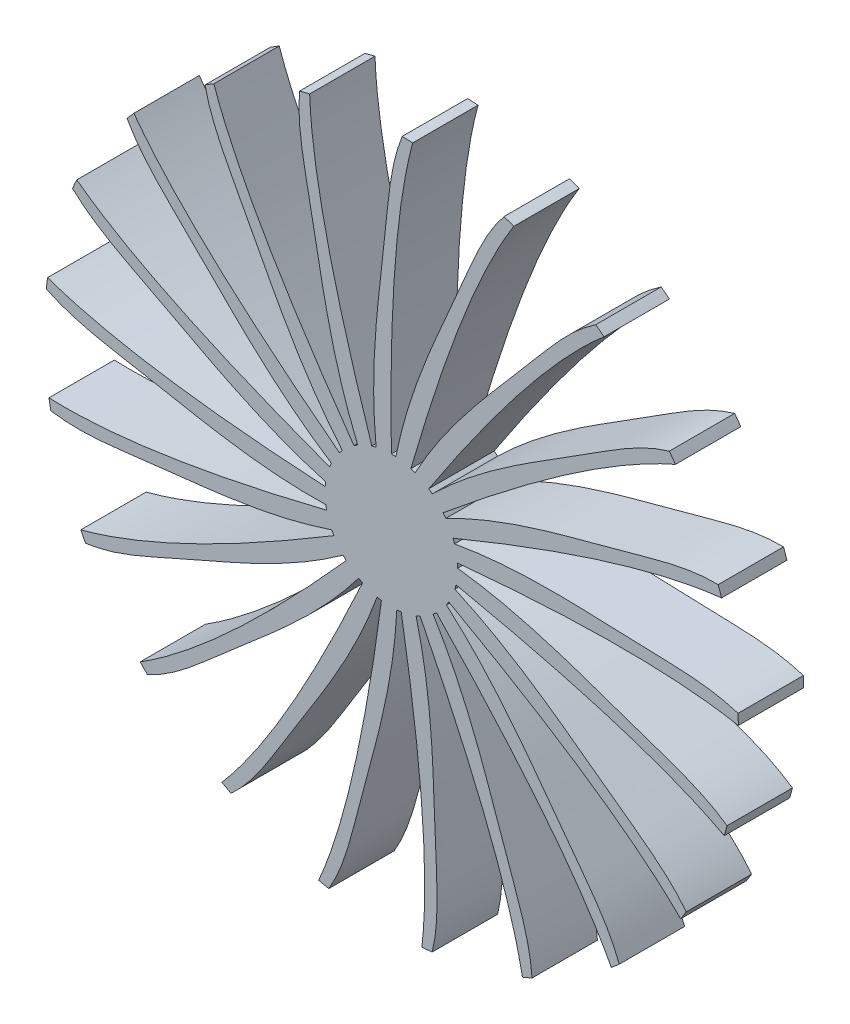
SolidWorks part; units mm, degrees
ref_plane "Front Plane" through (0, 0, 0) normal (0, 0, 1) x (1, 0, 0)
ref_plane "Top Plane" through (0, 0, 0) normal (0, 1, 0) x (1, 0, 0)
ref_plane "Right Plane" through (0, 0, 0) normal (1, 0, 0) x (0, 0, -1)
sketch "Sketch1" plane through (0, 0, 0) normal (0, 0, 1) x (1, 0, 0)
  line L0 (0, 30.4353) -> (0, 70.6877) construction
  arc A0 (9.785, 158.9473) -> (5, 159.1697) centre (0, 0) ccw
  arc A1 (-15.0149, -26.4738) -> (-13.2054, -27.4213) centre (0, 0) ccw
  arc A2 (56.2008, 149.0016) -> (51.694, 150.6245) centre (0, 0) ccw
  arc A3 (97.6229, 125.8164) -> (93.7947, 128.6956) centre (0, 0) ccw
  arc A4 (130.3708, 91.4518) -> (127.5613, 95.3315) centre (0, 0) ccw
  arc A5 (151.5347, 48.9614) -> (149.9936, 53.4969) centre (0, 0) ccw
  arc A6 (159.2341, 2.1205) -> (159.0983, 6.9087) centre (0, 0) ccw
  arc A7 (152.7848, -44.9087) -> (154.0664, -40.2932) centre (0, 0) ccw
  arc A8 (132.7599, -87.9477) -> (135.345, -83.915) centre (0, 0) ccw
  arc A9 (100.9387, -123.1721) -> (104.5976, -120.0805) centre (0, 0) ccw
  arc A10 (60.1487, -147.4521) -> (64.5563, -145.5764) centre (0, 0) ccw
  arc A11 (14.0142, -158.6304) -> (18.7789, -158.1371) centre (0, 0) ccw
  arc A12 (-33.3655, -155.7136) -> (-28.6672, -156.6467) centre (0, 0) ccw
  arc A13 (-77.7806, -138.961) -> (-73.566, -141.2375) centre (0, 0) ccw
  arc A14 (-115.2845, -109.8612) -> (-111.9282, -113.2788) centre (0, 0) ccw
  arc A15 (-142.5449, -70.9996) -> (-140.345, -75.2547) centre (0, 0) ccw
  arc A16 (-157.1395, -25.8295) -> (-156.2916, -30.544) centre (0, 0) ccw
  arc A17 (-157.7716, 21.6357) -> (-158.351, 16.8808) centre (0, 0) ccw
  arc A18 (-144.385, 67.1785) -> (-146.3402, 62.8056) centre (0, 0) ccw
  arc A19 (-118.1692, 106.7522) -> (-121.3264, 103.1498) centre (0, 0) ccw
  arc A20 (-81.4535, 136.8405) -> (-85.5323, 134.3288) centre (0, 0) ccw
  arc A21 (-37.5003, 154.7699) -> (-42.1382, 153.572) centre (0, 0) ccw
  arc A22 (-22.1511, -20.8719) -> (-20.7013, -22.3107) centre (0, 0) ccw
  arc A23 (2.5073, -30.3319) -> (4.5361, -30.0954) centre (0, 0) ccw
  arc A24 (-6.5446, -29.7233) -> (-4.5361, -30.0954) centre (0, 0) ccw
  arc A25 (11.3364, -28.2453) -> (13.2054, -27.4213) centre (0, 0) ccw
  arc A26 (19.1582, -23.649) -> (20.7013, -22.3107) centre (0, 0) ccw
  arc A27 (25.2777, -16.9513) -> (26.3578, -15.2177) centre (0, 0) ccw
  arc A28 (29.1511, -8.7475) -> (29.6722, -6.7725) centre (0, 0) ccw
  arc A29 (-27.3191, -13.4154) -> (-26.3578, -15.2177) centre (0, 0) ccw
  arc A30 (-30.0597, -4.767) -> (-29.6722, -6.7725) centre (0, 0) ccw
  arc A31 (-30.1293, 4.3051) -> (-30.3502, 2.2744) centre (0, 0) ccw
  arc A32 (-22.4689, 20.5295) -> (-23.7953, 18.9761) centre (0, 0) ccw
  arc A33 (-27.5218, 12.9946) -> (-28.3314, 11.1193) centre (0, 0) ccw
  arc A34 (-15.4195, 26.2402) -> (-17.1448, 25.1468) centre (0, 0) ccw
  arc A35 (-7, 29.6194) -> (-8.971, 29.0832) centre (0, 0) ccw
  arc A36 (2.0415, 30.3668) -> (0, 30.4353) centre (0, 0) ccw
  arc A37 (10.9015, 28.4159) -> (8.971, 29.0832) centre (0, 0) ccw
  arc A38 (18.7929, 23.9402) -> (17.1448, 25.1468) centre (0, 0) ccw
  arc A39 (25.0145, 17.3373) -> (23.7953, 18.9761) centre (0, 0) ccw
  arc A40 (29.0135, 9.1939) -> (28.3314, 11.1193) centre (0, 0) ccw
  arc A41 (30.4344, 0.2336) -> (30.3502, 2.2744) centre (0, 0) ccw
  spline S0 degree 3 poles (-7, 29.6194) (-9.6924, 56.721) (-6.6225, 83.7904) (-1.6795, 126.6297) (-0.3347, 146.1346) (5, 159.1697) knots 0 0 0 0 0.569376 0.669376 1 1 1 1
  spline S1 degree 2 poles (0, 30.4353) (-1.6186, 116.9207) (9.785, 158.9473) knots 0 0 0 1 1 1
  spline S2 degree 3 poles (2.0415, 30.3668) (7.457, 57.0579) (18.3694, 82.0198) (35.7199, 121.4989) (42.7542, 139.7409) (51.694, 150.6245) knots 0 0 0 0 0.569376 0.669376 1 1 1 1
  spline S3 degree 2 poles (8.971, 29.0832) (32.9163, 112.2034) (56.2008, 149.0016) knots 0 0 0 1 1 1
  spline S4 degree 3 poles (10.9015, 28.4159) (23.9438, 52.325) (41.7291, 72.9615) (69.9454, 105.5725) (82.0441, 120.9306) (93.7947, 128.6956) knots 0 0 0 0 0.569376 0.669376 1 1 1 1
  spline S5 degree 2 poles (17.1448, 25.1468) (64.5264, 97.5162) (97.6229, 125.8164) knots 0 0 0 1 1 1
  spline S6 degree 3 poles (18.7929, 23.9402) (38.3031, 42.9428) (61.3809, 57.4201) (97.9559, 80.2654) (114.044, 91.3751) (127.5613, 95.3315) knots 0 0 0 0 0.569376 0.669376 1 1 1 1
  spline S7 degree 2 poles (23.7953, 18.9761) (90.4031, 74.1644) (130.3708, 91.4518) knots 0 0 0 1 1 1
  spline S8 degree 3 poles (25.0145, 17.3373) (49.259, 29.7449) (75.5788, 36.7768) (117.2627, 47.8264) (135.9106, 53.7005) (149.9936, 53.4969) knots 0 0 0 0 0.569376 0.669376 1 1 1 1
  spline S9 degree 2 poles (28.3314, 11.1193) (108.2471, 44.2227) (151.5347, 48.9614) knots 0 0 0 1 1 1
  spline S10 degree 3 poles (29.0135, 9.1939) (55.8381, 13.9041) (83.0612, 12.8656) (126.1501, 11.1379) (145.701, 11.2544) (159.0983, 6.9087) knots 0 0 0 0 0.569376 0.669376 1 1 1 1
  spline S11 degree 2 poles (30.3502, 2.2744) (116.4728, 10.3516) (159.2341, 2.1205) knots 0 0 0 1 1 1
  spline S12 degree 3 poles (30.4344, 0.2336) (57.4556, -3.1722) (83.1632, -12.1887) (123.8285, -26.5403) (142.5452, -32.1918) (154.0664, -40.2932) knots 0 0 0 0 0.569376 0.669376 1 1 1 1
  spline S13 degree 2 poles (29.6722, -6.7725) (114.3494, -24.4392) (152.7848, -44.9087) knots 0 0 0 1 1 1
  spline S14 degree 3 poles (29.1511, -8.7475) (53.968, -19.9666) (75.8759, -36.16) (110.5043, -61.8603) (126.7236, -72.7775) (135.345, -83.915) knots 0 0 0 0 0.569376 0.669376 1 1 1 1
  spline S15 degree 2 poles (26.3578, -15.2177) (102.0656, -57.0586) (132.7599, -87.9477) knots 0 0 0 1 1 1
  spline S16 degree 3 poles (25.2777, -16.9513) (45.6851, -34.9869) (61.8466, -56.9183) (87.3612, -91.6838) (99.6421, -106.8967) (104.5976, -120.0805) knots 0 0 0 0 0.569376 0.669376 1 1 1 1
  spline S17 degree 2 poles (20.7013, -22.3107) (80.7128, -84.608) (100.9387, -123.1721) knots 0 0 0 1 1 1
  spline S18 degree 3 poles (19.1582, -23.649) (33.3429, -46.8984) (42.3219, -72.6192) (56.4558, -113.3607) (63.707, -131.5176) (64.5563, -145.5764) knots 0 0 0 0 0.569376 0.669376 1 1 1 1
  spline S19 degree 2 poles (13.2054, -27.4213) (52.1883, -104.6396) (60.1487, -147.4521) knots 0 0 0 1 1 1
  spline S20 degree 3 poles (11.3364, -28.2453) (18.038, -54.6429) (19.0368, -81.8675) (20.5339, -124.965) (22.1112, -144.4526) (18.7789, -158.1371) knots 0 0 0 0 0.569376 0.669376 1 1 1 1
  spline S21 degree 2 poles (4.5361, -30.0954) (19.0267, -115.3736) (14.0142, -158.6304) knots 0 0 0 1 1 1
  spline S22 degree 3 poles (2.5073, -30.3319) (1.1304, -57.532) (-5.9398, -83.8416) (-17.2124, -125.4657) (-21.4493, -144.5523) (-28.6672, -156.6467) knots 0 0 0 0 0.569376 0.669376 1 1 1 1
  spline S23 degree 2 poles (-4.5361, -30.0954) (-15.8256, -115.856) (-33.3655, -155.7136) knots 0 0 0 1 1 1
  spline S24 degree 3 poles (-6.5446, -29.7233) (-15.8777, -55.3092) (-30.3886, -78.3659) (-53.4294, -114.8181) (-63.1039, -131.808) (-73.566, -141.2375) knots 0 0 0 0 0.569376 0.669376 1 1 1 1
  spline S25 degree 2 poles (-13.2054, -27.4213) (-49.2716, -106.0442) (-77.7806, -138.961) knots 0 0 0 1 1 1
  spline S26 degree 3 poles (-15.0149, -26.4738) (-31.475, -48.1719) (-52.1373, -65.9271) (-84.8989, -93.9685) (-99.1515, -107.3519) (-111.9282, -113.2788) knots 0 0 0 0 0.569376 0.669376 1 1 1 1
  spline S27 degree 2 poles (-20.7013, -22.3107) (-78.3397, -86.8099) (-115.2845, -109.8612) knots 0 0 0 1 1 1
  spline S28 degree 3 poles (-22.1511, -20.8719) (-44.2756, -36.7544) (-69.2534, -47.6304) (-108.8248, -64.7693) (-126.389, -73.3571) (-140.345, -75.2547) knots 0 0 0 0 0.569376 0.669376 1 1 1 1
  spline S29 degree 2 poles (-26.3578, -15.2177) (-100.447, -59.8621) (-142.5449, -70.9996) knots 0 0 0 1 1 1
  spline S30 degree 3 poles (-27.3191, -13.4154) (-53.1421, -22.071) (-80.216, -25.1016) (-123.0811, -29.8152) (-142.3963, -32.8443) (-156.2916, -30.544) knots 0 0 0 0 0.569376 0.669376 1 1 1 1
  spline S31 degree 2 poles (-29.6722, -6.7725) (-113.6291, -27.5954) (-157.1395, -25.8295) knots 0 0 0 1 1 1
  spline S32 degree 3 poles (-30.0597, -4.767) (-57.2867, -5.4266) (-84.051, -0.3423) (-126.4011, 7.7882) (-145.751, 10.5869) (-158.351, 16.8808) knots 0 0 0 0 0.569376 0.669376 1 1 1 1
  spline S33 degree 2 poles (-30.3502, 2.2744) (-116.7147, 7.1234) (-157.7716, 21.6357) knots 0 0 0 1 1 1
  spline S34 degree 3 poles (-30.1293, 4.3051) (-56.3411, 11.7001) (-80.4178, 24.4474) (-118.4898, 44.6996) (-136.1552, 53.0775) (-146.3402, 62.8056) knots 0 0 0 0 0.569376 0.669376 1 1 1 1
  spline S35 degree 2 poles (-28.3314, 11.1193) (-109.4298, 41.2092) (-144.385, 67.1785) knots 0 0 0 1 1 1
  spline S36 degree 3 poles (-27.5218, 12.9946) (-50.3894, 27.7871) (-69.639, 47.0648) (-100.0502, 77.6392) (-114.4613, 90.8518) (-121.3264, 103.1498) knots 0 0 0 0 0.569376 0.669376 1 1 1 1
  spline S37 degree 2 poles (-23.7953, 18.9761) (-92.4215, 71.6334) (-118.1692, 106.7522) knots 0 0 0 1 1 1
  spline S38 degree 3 poles (-22.4689, 20.5295) (-39.9603, 41.4051) (-52.6726, 65.5003) (-72.7207, 103.6802) (-82.5971, 120.5536) (-85.5323, 134.3288) knots 0 0 0 0 0.569376 0.669376 1 1 1 1
  spline S39 degree 2 poles (-17.1448, 25.1468) (-67.2012, 95.6926) (-81.4535, 136.8405) knots 0 0 0 1 1 1
  spline S40 degree 3 poles (-15.4195, 26.2402) (-25.9806, 51.3441) (-31.0259, 78.1158) (-38.9297, 120.5088) (-43.3937, 139.5437) (-42.1382, 153.572) knots 0 0 0 0 0.569376 0.669376 1 1 1 1
  spline S41 degree 2 poles (-8.971, 29.0832) (-36.0097, 111.2491) (-37.5003, 154.7699) knots 0 0 0 1 1 1
  point P112 (0, 0)
  dimension "D1" = 21
  dimension "D3" = 90.7833
  dimension "D2" = 7
extrude "Boss-Extrude1" add sketch "Sketch1" against normal blind 30
